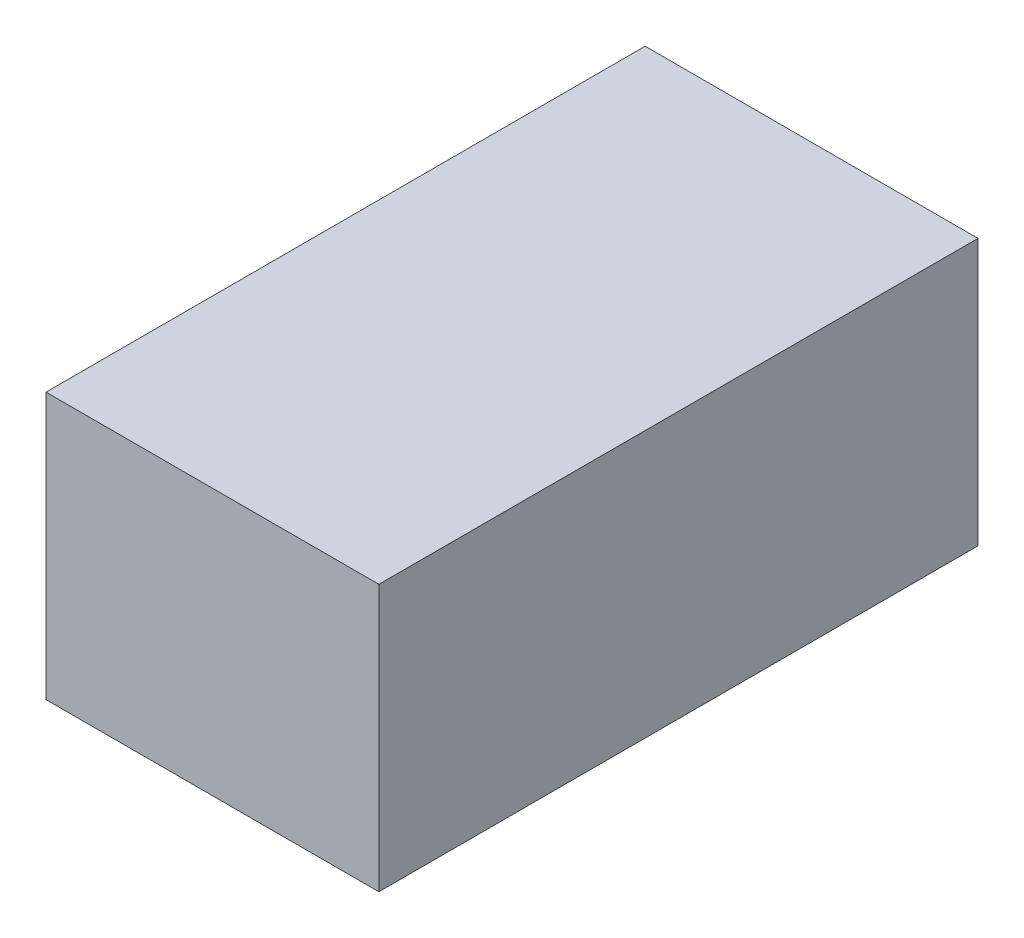
SolidWorks part; units mm, degrees
ref_plane "Front Plane" through (0, 0, 0) normal (0, 0, 1) x (1, 0, 0)
ref_plane "Top Plane" through (0, 0, 0) normal (0, 1, 0) x (1, 0, 0)
ref_plane "Right Plane" through (0, 0, 0) normal (1, 0, 0) x (0, 0, -1)
sketch "Sketch1" plane through (0, 0, 0) normal (0, 0, 1) x (1, 0, 0)
  line L1 (0, 0) -> (30, 0)
  line L2 (0, 0) -> (0, 24)
  line L3 (0, 24) -> (30, 24)
  line L4 (30, 0) -> (30, 24)
  dimension "D1" = 24
  dimension "D2" = 30
extrude "Boss-Extrude1" add sketch "Sketch1" along normal blind 54
sketch "Sketch3" plane through (0, 0, 0) normal (0, 0, -1) x (-1, 0, 0)
  line L0 (-15, 24) -> (-15, 0) construction
  line L1 (-30, 24) -> (0, 24) construction
  line L2 (0, 0) -> (-30, 0) construction
  line L4 (-30, 0) -> (-30, 24) construction
  line L5 (-30, 12) -> (0, 12) construction
  line L6 (0, 24) -> (0, 0) construction
  point P6 (-15, 12)
  point P13 (0, 0)
